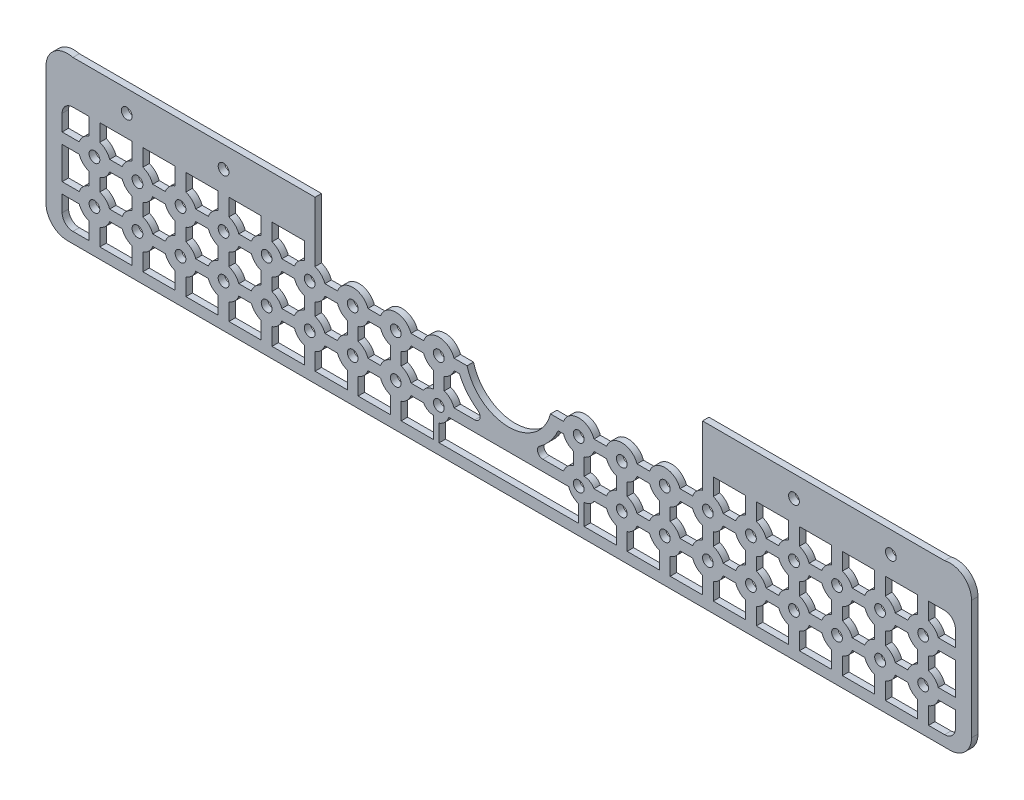
SolidWorks part; units mm, degrees
ref_plane "Front Plane" through (0, 0, 0) normal (0, 0, 1) x (1, 0, 0)
ref_plane "Top Plane" through (0, 0, 0) normal (0, 1, 0) x (1, 0, 0)
ref_plane "Right Plane" through (0, 0, 0) normal (1, 0, 0) x (0, 0, -1)
sketch "Sketch1" plane through (0, 0, 0) normal (0, 0, 1) x (1, 0, 0)
  line L0 (-40, 20) -> (-40, 55) construction
  line L1 (409.9997, -75) -> (-409.9997, -75) construction
  line L4 (-429.9997, -55) -> (-429.9997, 55.635)
  line L5 (425.0106, -74.9397) -> (-424.8517, 74.9116) construction
  line L6 (425.148, 74.1538) -> (-429.9997, -75) construction
  line L8 (-60, 75) -> (-405, 75) construction
  line L9 (-415, -55) -> (-415, -40)
  line L15 (405, -65) -> (-405, -65) construction
  line L16 (-405, 35) -> (-390, 35)
  line L17 (0, -20) -> (0, -40)
  line L20 (-415, 10) -> (-415, 25)
  line L21 (-400, 5) -> (-415, 5) construction
  line L25 (0, -65) -> (0, -75)
  line L26 (0, 75) -> (0, -75) construction
  line L27 (-50, 95) -> (50, 95) construction
  line L28 (-399.1421, 10) -> (-415, 10)
  line L29 (-380, 19.1421) -> (-380, 35)
  line L30 (-399.1421, 0) -> (-415, 0)
  line L31 (-390, 19.1421) -> (-390, 35)
  line L32 (-415, -15) -> (0, -15) construction
  line L33 (-399.1421, -30) -> (-415, -30)
  line L34 (0, -75) -> (-409.9997, -75)
  line L35 (-64.6988, -49.1887) -> (-64.6988, -65)
  line L37 (-399.1421, -40) -> (-415, -40)
  line L38 (-390, -49.1421) -> (-390, -65)
  line L39 (-380, -49.1421) -> (-380, -65)
  line L40 (-415, -30) -> (-415, 0)
  line L41 (-405, -65) -> (-390, -65)
  line L42 (-380, -65) -> (405, -65) construction
  line L43 (-390, -9.1421) -> (-390, -20.8579)
  line L44 (-380, -9.1421) -> (-380, -20.8579)
  line L45 (-350, 19.1421) -> (-350, 35)
  line L46 (-340, 19.1421) -> (-340, 35)
  line L47 (-350, -49.1421) -> (-350, -65)
  line L48 (-340, -49.1421) -> (-340, -65)
  line L49 (-340, -9.1421) -> (-340, -20.8579)
  line L50 (-350, -9.1421) -> (-350, -20.8579)
  line L51 (-359.1421, 10) -> (-370.8579, 10)
  line L52 (-359.1421, 0) -> (-370.8579, 0)
  line L53 (-359.1421, -30) -> (-370.8579, -30)
  line L54 (-359.1421, -40) -> (-370.8579, -40)
  line L55 (-319.1421, 10) -> (-330.8579, 10)
  line L56 (-319.1421, 0) -> (-330.8579, 0)
  line L57 (-310, 19.1421) -> (-310, 35)
  line L58 (-300, 19.1421) -> (-300, 35)
  line L59 (-310, -9.1421) -> (-310, -20.8579)
  line L60 (-300, -9.1421) -> (-300, -20.8579)
  line L61 (-300, -49.1421) -> (-300, -65)
  line L62 (-310, -49.1421) -> (-310, -65)
  line L63 (-319.1421, -30) -> (-330.8579, -30)
  line L64 (-319.1421, -40) -> (-330.8579, -40)
  line L65 (-279.1421, 10) -> (-290.8579, 10)
  line L66 (-279.1421, 0) -> (-290.8579, 0)
  line L67 (-270, 19.1421) -> (-270, 35)
  line L68 (-260, 19.1421) -> (-260, 35)
  line L69 (-270, -9.1421) -> (-270, -20.8579)
  line L70 (-260, -9.1421) -> (-260, -20.8579)
  line L71 (-260, -49.1421) -> (-260, -65)
  line L72 (-270, -49.1421) -> (-270, -65)
  line L73 (-279.1421, -30) -> (-290.8579, -30)
  line L74 (-279.1421, -40) -> (-290.8579, -40)
  line L75 (-239.1421, 10) -> (-250.8579, 10)
  line L76 (-239.1421, 0) -> (-250.8579, 0)
  line L77 (-230, 19.1421) -> (-230, 35)
  line L78 (-220, 19.1421) -> (-220, 35)
  line L79 (-230, -9.1421) -> (-230, -20.8579)
  line L80 (-220, -9.1421) -> (-220, -20.8579)
  line L81 (-220, -49.1421) -> (-220, -65)
  line L82 (-230, -49.1421) -> (-230, -65)
  line L83 (-239.1421, -30) -> (-250.8579, -30)
  line L84 (-239.1421, -40) -> (-250.8579, -40)
  line L85 (-199.1421, 10) -> (-210.8579, 10)
  line L86 (-199.1421, 0) -> (-210.8579, 0)
  line L87 (-190, 19.1421) -> (-190, 35)
  line L88 (-180, 19.1421) -> (-180, 35)
  line L89 (-190, -9.1421) -> (-190, -20.8579)
  line L90 (-180, -9.1421) -> (-180, -20.8579)
  line L91 (-180, -49.1421) -> (-180, -65)
  line L92 (-190, -49.1421) -> (-190, -65)
  line L93 (-199.1421, -30) -> (-210.8579, -30)
  line L94 (-199.1421, -40) -> (-210.8579, -40)
  line L95 (-159.1421, 10) -> (-170.8579, 10)
  line L96 (-159.1421, 0) -> (-170.8579, 0)
  line L99 (-150, -9.1421) -> (-150, -20.8579)
  line L100 (-140, -9.1421) -> (-140, -20.8579)
  line L101 (-140, -49.1421) -> (-140, -65)
  line L102 (-150, -49.1421) -> (-150, -65)
  line L103 (-159.1421, -30) -> (-170.8579, -30)
  line L104 (-159.1421, -40) -> (-170.8579, -40)
  line L105 (-119.1421, 10) -> (-130.8579, 10)
  line L106 (-119.1421, 0) -> (-130.8579, 0)
  line L109 (-110, -9.1421) -> (-110, -20.8579)
  line L110 (-100, -9.1421) -> (-100, -20.8579)
  line L111 (-100, -49.1421) -> (-100, -65)
  line L112 (-110, -49.1421) -> (-110, -65)
  line L113 (-119.1421, -30) -> (-130.8579, -30)
  line L114 (-119.1421, -40) -> (-130.8579, -40)
  line L115 (-79.1421, 10) -> (-90.8579, 10)
  line L116 (-79.1421, 0) -> (-90.8579, 0)
  line L118 (-64.6988, -65) -> (0, -65)
  line L119 (-70, -9.1421) -> (-70, -24.5796)
  line L122 (-70, -45.4204) -> (-70, -65)
  line L123 (-79.1421, -30) -> (-90.8579, -30)
  line L124 (-79.1421, -40) -> (-90.8579, -40)
  line L125 (-380, 35) -> (-350, 35)
  line L126 (-380, -65) -> (-350, -65)
  line L127 (-340, -65) -> (-310, -65)
  line L128 (-340, 35) -> (-310, 35)
  line L129 (-300, -65) -> (-270, -65)
  line L130 (-300, 35) -> (-270, 35)
  line L131 (-260, -65) -> (-230, -65)
  line L132 (-260, 35) -> (-230, 35)
  line L133 (-220, -65) -> (-190, -65)
  line L134 (-220, 35) -> (-190, 35)
  line L135 (-180, -65) -> (-150, -65)
  line L137 (-140, -65) -> (-110, -65)
  line L139 (-100, -65) -> (-70, -65)
  line L141 (0, -40) -> (-55.7022, -40)
  line L143 (-60, -9.1421) -> (-60, -20.8579)
  line L147 (-50.8579, -30) -> (-31.6228, -30)
  line L149 (-50.8579, 0) -> (-45.8258, 0)
  line L150 (-50.8579, 10) -> (-48.9898, 10)
  line L167 (-48.9898, 10) -> (-38.7298, 10)
  line L168 (-140, 35) -> (-110, 35) [skipped]
  line L170 (-405, 75) -> (-180, 75)
  line L172 (-86.7, 35) -> (-70, 35) [skipped]
  line L175 (-180, 75) -> (-180, 35)
  line L176 (-180, 35) -> (-166.4336, 35) [skipped]
  arc A0 (-40, 20) -> (0, -20) centre (0, 20) ccw construction
  circle A1 centre (0, 20) radius 30 construction
  arc A4 (-409.9997, -75) -> (-429.9997, -55) centre (-409.9997, -55) cw
  arc A5 (-429.9997, 55.635) -> (-405, 75) centre (-409.9997, 55.635) cw
  arc A14 (-405, -65) -> (-415, -55) centre (-405, -55) cw
  arc A15 (-64.6988, -49.1887) -> (-55.7022, -40) centre (-69.9997, -35) ccw
  arc A16 (-50.8579, 10) -> (-60, 19.1421) centre (-65, 5) ccw
  arc A17 (-60, -9.1421) -> (-50.8579, 0) centre (-65, 5) ccw
  arc A19 (-415, 25) -> (-405, 35) centre (-405, 25) cw
  arc A20 (-390, 19.1421) -> (-399.1421, 10) centre (-385, 5) ccw
  circle A21 centre (-385, 5) radius 5
  arc A22 (-60, -20.8579) -> (-50.8579, -30) centre (-65, -35) cw
  arc A23 (-28.748, -20.9091) -> (-45.8258, 0) centre (0, 20) cw
  circle A26 centre (-354.9997, 55) radius 5
  circle A27 centre (-265, 55) radius 5
  arc A30 (-399.1421, 0) -> (-390, -9.1421) centre (-385, 5) ccw
  arc A31 (-390, -49.1421) -> (-399.1421, -40) centre (-385, -35) cw
  circle A32 centre (-385, -35) radius 5
  arc A33 (-399.1421, -30) -> (-390, -20.8579) centre (-385, -35) cw
  arc A34 (-380, -9.1421) -> (-370.8579, 0) centre (-385, 5) ccw
  arc A35 (-380, -20.8579) -> (-370.8579, -30) centre (-385, -35) cw
  arc A36 (-350, 19.1421) -> (-359.1421, 10) centre (-345, 5) ccw
  arc A37 (-359.1421, 0) -> (-350, -9.1421) centre (-345, 5) ccw
  arc A38 (-370.8579, 10) -> (-380, 19.1421) centre (-385, 5) ccw
  arc A39 (-370.8579, -40) -> (-380, -49.1421) centre (-385, -35) cw
  arc A40 (-359.1421, -30) -> (-350, -20.8579) centre (-345, -35) cw
  arc A41 (-350, -49.1421) -> (-359.1421, -40) centre (-345, -35) cw
  arc A43 (-31.6228, -30) -> (-28.748, -20.9091) centre (-31.6228, -25) ccw
  arc A44 (-330.8579, 10) -> (-340, 19.1421) centre (-345, 5) ccw
  arc A45 (-340, -9.1421) -> (-330.8579, 0) centre (-345, 5) ccw
  arc A46 (-340, -20.8579) -> (-330.8579, -30) centre (-345, -35) cw
  arc A47 (-330.8579, -40) -> (-340, -49.1421) centre (-345, -35) cw
  arc A48 (-310, 19.1421) -> (-319.1421, 10) centre (-305, 5) ccw
  arc A49 (-290.8579, 10) -> (-300, 19.1421) centre (-305, 5) ccw
  arc A50 (-300, -9.1421) -> (-290.8579, 0) centre (-305, 5) ccw
  arc A51 (-319.1421, 0) -> (-310, -9.1421) centre (-305, 5) ccw
  arc A52 (-300, -20.8579) -> (-290.8579, -30) centre (-305, -35) cw
  arc A53 (-290.8579, -40) -> (-300, -49.1421) centre (-305, -35) cw
  arc A54 (-310, -49.1421) -> (-319.1421, -40) centre (-305, -35) cw
  arc A55 (-319.1421, -30) -> (-310, -20.8579) centre (-305, -35) cw
  arc A56 (-270, 19.1421) -> (-279.1421, 10) centre (-265, 5) ccw
  arc A57 (-250.8579, 10) -> (-260, 19.1421) centre (-265, 5) ccw
  arc A58 (-260, -9.1421) -> (-250.8579, 0) centre (-265, 5) ccw
  arc A59 (-279.1421, 0) -> (-270, -9.1421) centre (-265, 5) ccw
  arc A60 (-260, -20.8579) -> (-250.8579, -30) centre (-265, -35) cw
  arc A61 (-250.8579, -40) -> (-260, -49.1421) centre (-265, -35) cw
  arc A62 (-270, -49.1421) -> (-279.1421, -40) centre (-265, -35) cw
  arc A63 (-279.1421, -30) -> (-270, -20.8579) centre (-265, -35) cw
  arc A64 (-230, 19.1421) -> (-239.1421, 10) centre (-225, 5) ccw
  arc A65 (-210.8579, 10) -> (-220, 19.1421) centre (-225, 5) ccw
  arc A66 (-220, -9.1421) -> (-210.8579, 0) centre (-225, 5) ccw
  arc A67 (-239.1421, 0) -> (-230, -9.1421) centre (-225, 5) ccw
  arc A68 (-220, -20.8579) -> (-210.8579, -30) centre (-225, -35) cw
  arc A69 (-210.8579, -40) -> (-220, -49.1421) centre (-225, -35) cw
  arc A70 (-230, -49.1421) -> (-239.1421, -40) centre (-225, -35) cw
  arc A71 (-239.1421, -30) -> (-230, -20.8579) centre (-225, -35) cw
  arc A72 (-190, 19.1421) -> (-199.1421, 10) centre (-185, 5) ccw
  arc A73 (-170.8579, 10) -> (-180, 19.1421) centre (-185, 5) ccw
  arc A74 (-180, -9.1421) -> (-170.8579, 0) centre (-185, 5) ccw
  arc A75 (-199.1421, 0) -> (-190, -9.1421) centre (-185, 5) ccw
  arc A76 (-180, -20.8579) -> (-170.8579, -30) centre (-185, -35) cw
  arc A77 (-170.8579, -40) -> (-180, -49.1421) centre (-185, -35) cw
  arc A78 (-190, -49.1421) -> (-199.1421, -40) centre (-185, -35) cw
  arc A79 (-199.1421, -30) -> (-190, -20.8579) centre (-185, -35) cw
  arc A80 (-150, 19.1421) -> (-159.1421, 10) centre (-145, 5) ccw
  arc A81 (-130.8579, 10) -> (-140, 19.1421) centre (-145, 5) ccw
  arc A82 (-140, -9.1421) -> (-130.8579, 0) centre (-145, 5) ccw
  arc A83 (-159.1421, 0) -> (-150, -9.1421) centre (-145, 5) ccw
  arc A84 (-140, -20.8579) -> (-130.8579, -30) centre (-145, -35) cw
  arc A85 (-130.8579, -40) -> (-140, -49.1421) centre (-145, -35) cw
  arc A86 (-150, -49.1421) -> (-159.1421, -40) centre (-145, -35) cw
  arc A87 (-159.1421, -30) -> (-150, -20.8579) centre (-145, -35) cw
  arc A88 (-110, 19.1421) -> (-119.1421, 10) centre (-105, 5) ccw
  arc A89 (-90.8579, 10) -> (-100, 19.1421) centre (-105, 5) ccw
  arc A90 (-100, -9.1421) -> (-90.8579, 0) centre (-105, 5) ccw
  arc A91 (-119.1421, 0) -> (-110, -9.1421) centre (-105, 5) ccw
  arc A92 (-100, -20.8579) -> (-90.8579, -30) centre (-105, -35) cw
  arc A93 (-90.8579, -40) -> (-100, -49.1421) centre (-105, -35) cw
  arc A94 (-110, -49.1421) -> (-119.1421, -40) centre (-105, -35) cw
  arc A95 (-119.1421, -30) -> (-110, -20.8579) centre (-105, -35) cw
  arc A96 (-70, 19.1421) -> (-79.1421, 10) centre (-65, 5) ccw
  arc A99 (-79.1421, 0) -> (-70, -9.1421) centre (-65, 5) ccw
  arc A102 (-70, -45.4204) -> (-79.1421, -40) centre (-69.9997, -35) cw
  arc A103 (-79.1421, -30) -> (-70, -24.5796) centre (-69.9997, -35) cw
  circle A105 centre (-345, 5) radius 5
  circle A106 centre (-345, -35) radius 5
  circle A107 centre (-305, 5) radius 5
  circle A108 centre (-305, -35) radius 5
  circle A109 centre (-265, 5) radius 5
  circle A110 centre (-265, -35) radius 5
  circle A111 centre (-225, 5) radius 5
  circle A112 centre (-225, -35) radius 5
  circle A113 centre (-185, 5) radius 5
  circle A114 centre (-185, -35) radius 5
  circle A115 centre (-145, 5) radius 5
  circle A116 centre (-145, -35) radius 5
  circle A117 centre (-105, 5) radius 5
  circle A118 centre (-105, -35) radius 5
  circle A119 centre (-65, 5) radius 5
  circle A120 centre (-65, -35) radius 5
  arc A122 (-150, 19.1421) -> (-140, 19.1421) centre (-145, 5) cw
  arc A124 (-110, 19.1421) -> (-100, 19.1421) centre (-105, 5) cw
  arc A125 (-70, 19.1421) -> (-60, 19.1421) centre (-65, 5) cw
  arc A126 (0, -20) -> (-38.7298, 10) centre (0, 20) cw
  point P0 (0, 0)
  point P11 (0, 50)
  point P13 (-38.681, 9.8128)
  point P30 (-40, 75)
  point P32 (0, 0)
  point P42 (0, 0)
  point P45 (0, -30)
  point P46 (0, 0)
  point P49 (0, 0)
  point P56 (0, 0)
  point P57 (0, 0)
  point P74 (0, 95)
  dimension "D3" = 80
  dimension "D4" = 60
  dimension "D6" = 55
  dimension "D7" = 75
  dimension "D10" = 75
  dimension "D11" = 30
  dimension "D12" = 10
  dimension "D15" = 75
  dimension "D20" = 10
  dimension "D21" = 10
  dimension "D25" = 5
  dimension "D26" = 11.7157
  dimension "D1" = 850
  dimension "D2" = 150
  dimension "D5" = 2
  dimension "D9" = 40
  dimension "D13" = 30
  dimension "D14" = 30
  dimension "D16" = 100
  dimension "D17" = 20
  dimension "D18" = 389.9997
  dimension "D19" = 20
  dimension "D22" = 20
  dimension "D23" = 75
  dimension "D24" = 225
  dimension "D27" = 10
  dimension "D28" = 5
  dimension "D29" = 11.7157
  dimension "D8" = 345
  dimension "D32" = 2
  dimension "D34" = 8
  dimension "D35" = 9
extrude "Boss-Extrude1" add sketch "Sketch1" along normal blind 6
mirror "Mirror1" about plane through (0, -20, 6) normal (-1, 0, 0) of "Boss-Extrude1"
